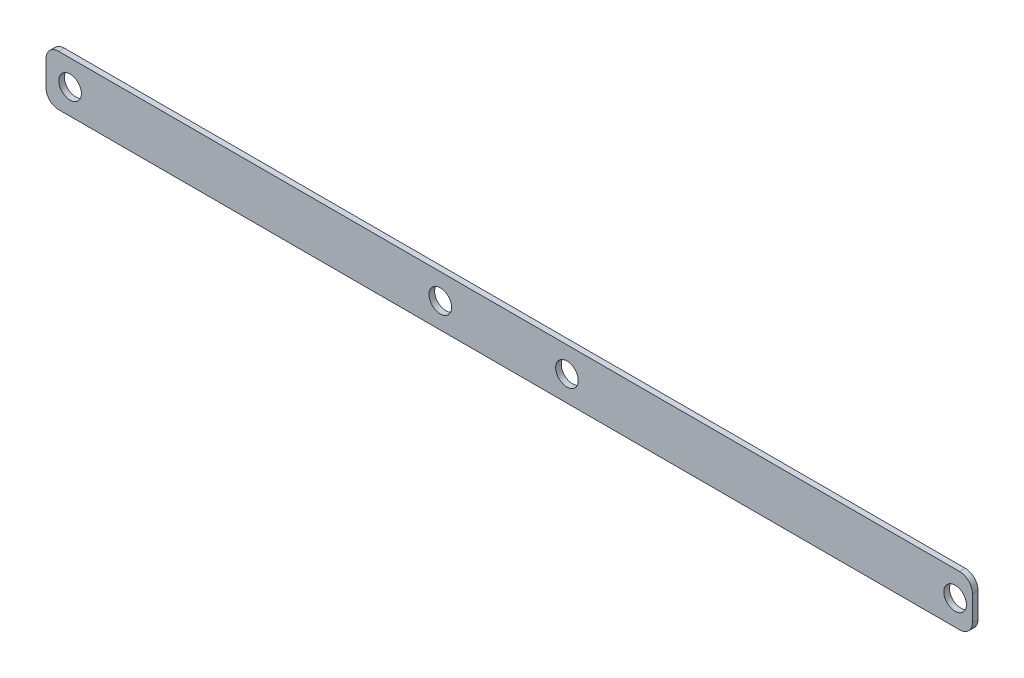
SolidWorks part; units mm, degrees
ref_plane "Front Plane" through (0, 0, 0) normal (0, 0, 1) x (1, 0, 0)
ref_plane "Top Plane" through (0, 0, 0) normal (0, 1, 0) x (1, 0, 0)
ref_plane "Right Plane" through (0, 0, 0) normal (1, 0, 0) x (0, 0, -1)
sketch "Sketch1" plane through (0, 0, 0) normal (0, 0, 1) x (1, 0, 0)
  line L0 (-156.1175, 2.1404) -> (164.8825, 2.1404)
  line L1 (169.3825, -2.3596) -> (169.3825, -11.3596)
  line L2 (164.8825, -15.8596) -> (-156.1175, -15.8596)
  line L3 (-160.6175, -11.3596) -> (-160.6175, -2.3596)
  arc A0 (164.8825, 2.1404) -> (169.3825, -2.3596) centre (164.8825, -2.3596) cw
  arc A1 (169.3825, -11.3596) -> (164.8825, -15.8596) centre (164.8825, -11.3596) cw
  arc A2 (-156.1175, -15.8596) -> (-160.6175, -11.3596) centre (-156.1175, -11.3596) cw
  arc A3 (-160.6175, -2.3596) -> (-156.1175, 2.1404) centre (-156.1175, -2.3596) cw
  circle A4 centre (-20.1515, -6.8763) radius 4.025
  circle A5 centre (24.9544, -6.8825) radius 4.025
  circle A6 centre (163.2416, -6.9016) radius 4.025
  circle A7 centre (-152.0361, -6.8581) radius 4.025
extrude "Boss-Extrude1" add sketch "Sketch1" along normal blind 2
